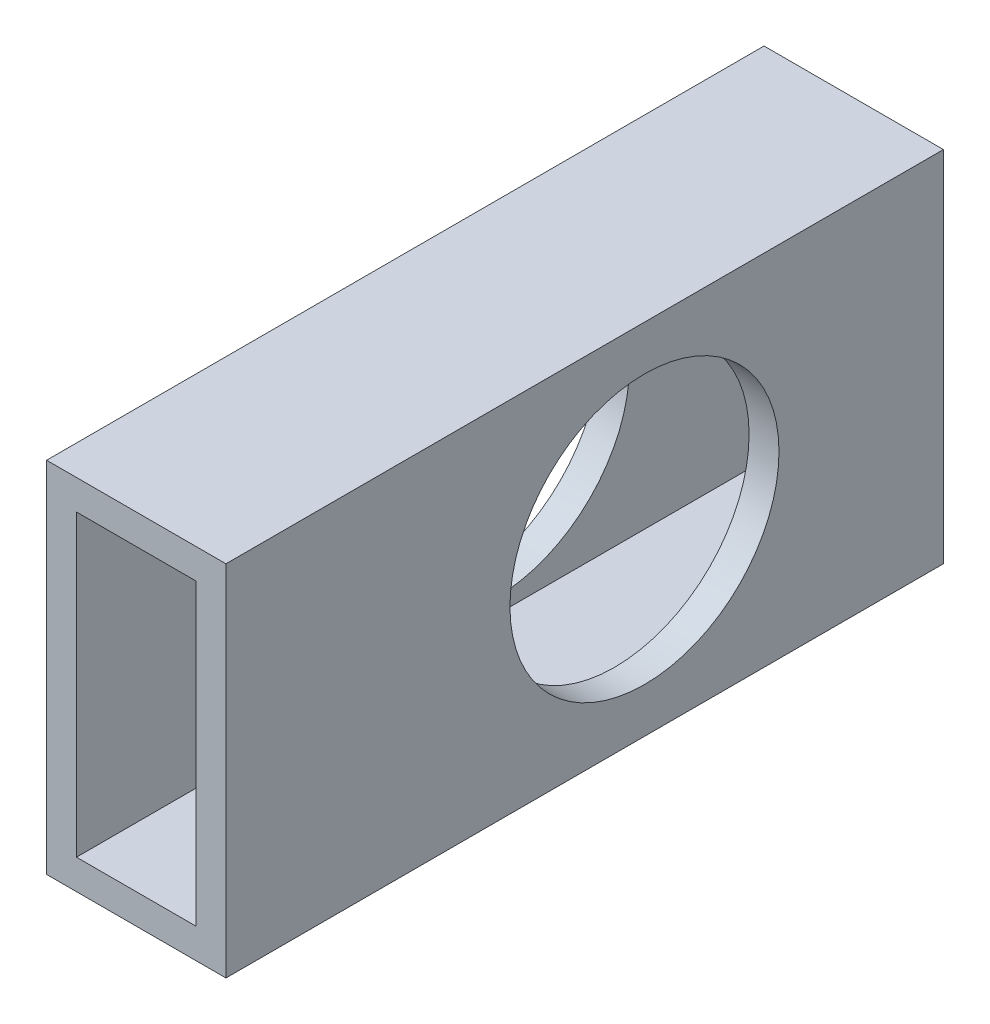
SolidWorks part; units mm, degrees
ref_plane "Front Plane" through (0, 0, 0) normal (0, 0, 1) x (1, 0, 0)
ref_plane "Top Plane" through (0, 0, 0) normal (0, 1, 0) x (1, 0, 0)
ref_plane "Right Plane" through (0, 0, 0) normal (1, 0, 0) x (0, 0, -1)
sketch "Sketch1" plane through (0, 0, 0) normal (0, 0, 1) x (1, 0, 0)
  line L1 (0, 0) -> (19.05, 0)
  line L2 (0, 0) -> (0, 38.1)
  line L3 (0, 38.1) -> (19.05, 38.1)
  line L4 (19.05, 0) -> (19.05, 38.1)
  dimension "D1" = 38.1
  dimension "D2" = 19.05
extrude "Extrude-Thin1" add sketch "Sketch1" along normal blind 76.2 thin thin type one direction reverse wall 3.175
sketch "Sketch2" plane through (19.05, 0, 0) normal (1, 0, 0) x (0, 0, -1)
  line L0 (-76.2, 38.1) -> (0, 38.1) construction
  line L1 (-76.2, 0) -> (-76.2, 38.1) construction
  circle A0 centre (-31.75, 19.05) radius 14.2875
  dimension "D1" = 19.05
  dimension "D2" = 44.45
extrude "Cut-Extrude1" cut sketch "Sketch2" against normal through all
